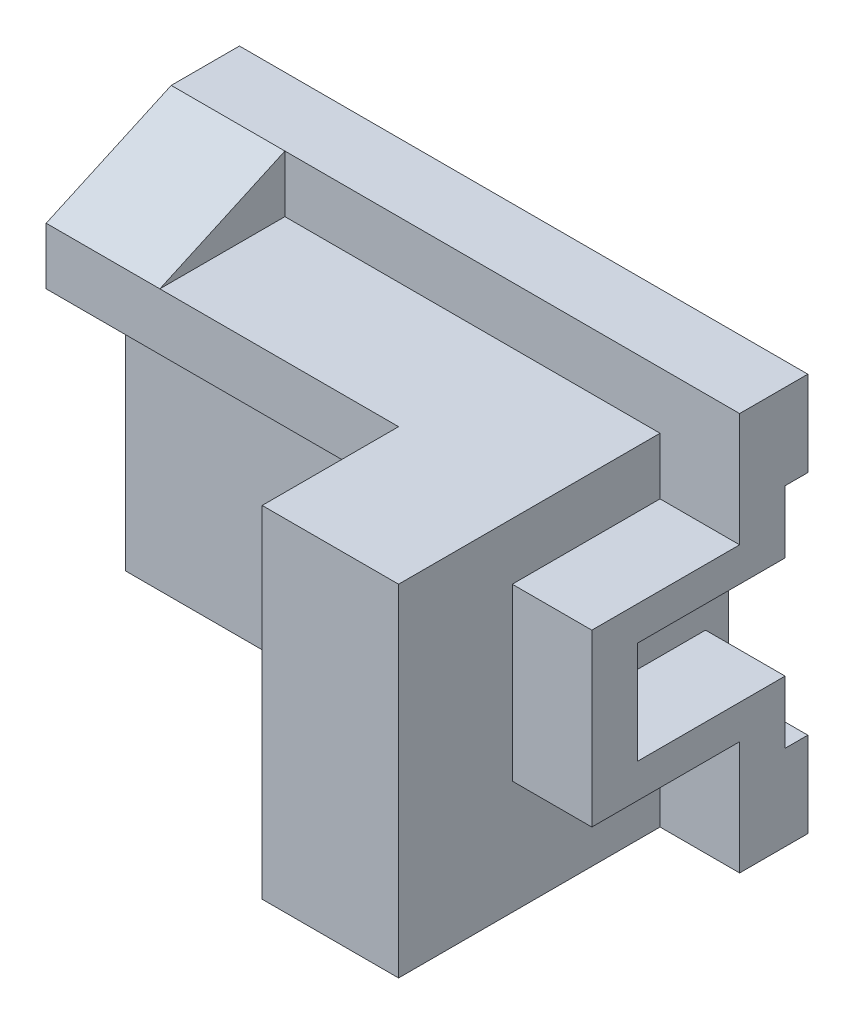
SolidWorks part; units mm, degrees
ref_plane "Спереди" through (0, 0, 0) normal (0, 0, 1) x (1, 0, 0)
ref_plane "Сверху" through (0, 0, 0) normal (0, 1, 0) x (1, 0, 0)
ref_plane "Справа" through (0, 0, 0) normal (1, 0, 0) x (0, 0, -1)
sketch "Эскиз1" plane through (0, 0, 0) normal (0, 0, 1) x (1, 0, 0)
  line L1 (-25, -17.5) -> (25, -17.5)
  line L2 (-25, -17.5) -> (-25, 17.5)
  line L3 (-25, 17.5) -> (25, 17.5)
  line L4 (25, -17.5) -> (25, 17.5)
  line L5 (-25, -17.5) -> (25, 17.5) construction
  line L6 (-25, 17.5) -> (25, -17.5) construction
  point P0 (0, 0)
  dimension "D1" = 35
  dimension "D2" = 50
extrude "Бобышка-Вытянуть1" add sketch "Эскиз1" along normal blind 6
sketch "Эскиз2" plane through (0, 0, 6) normal (0, 0, 1) x (1, 0, 0)
  line L0 (-25, -17.5) -> (25, -17.5) construction
  line L1 (18, -17.5) -> (6, -17.5)
  line L2 (18, -17.5) -> (18, 12.5)
  line L3 (18, 12.5) -> (6, 12.5)
  line L4 (6, -17.5) -> (6, 12.5)
  line L5 (25, -17.5) -> (25, 17.5) construction
  dimension "D1" = 7
  dimension "D2" = 12
  dimension "D3" = 30
extrude "Бобышка-Вытянуть2" add sketch "Эскиз2" along normal blind 23
sketch "Эскиз7" plane through (18, 0, 0) normal (1, 0, 0) x (0, 0, -1)
  line L0 (0, 0) -> (-29, 0) construction
  line L1 (-29, -17.5) -> (-29, 12.5) construction
  line L2 (-6, -17.5) -> (-6, 17.5) construction
  line L3 (-6, -7.5) -> (-19, -7.5)
  line L4 (-6, -7.5) -> (-6, 7.5)
  line L5 (-6, 7.5) -> (-19, 7.5)
  line L6 (-19, -7.5) -> (-19, 7.5)
  line L7 (-6, -7.5) -> (-19, 7.5) construction
  line L8 (-6, 7.5) -> (-19, -7.5) construction
  point P3 (-12.5, 0)
  dimension "D1" = 15
  dimension "D2" = 13
extrude "Бобышка-Вытянуть3" add sketch "Эскиз7" along normal up to surface (7 mm away) up to face at (25, 0, 3)
sketch "Эскиз8" plane through (25, 0, 0) normal (1, 0, 0) x (0, 0, -1)
  line L0 (0, 0) -> (-19, 0) construction
  line L1 (-19, 7.5) -> (-19, -7.5) construction
  line L2 (0, -17.5) -> (0, 17.5) construction
  line L3 (0, -4.5) -> (-15, -4.5)
  line L4 (0, -4.5) -> (0, 4.5)
  line L5 (0, 4.5) -> (-15, 4.5)
  line L6 (-15, -4.5) -> (-15, 4.5)
  line L7 (0, -4.5) -> (-15, 4.5) construction
  line L8 (0, 4.5) -> (-15, -4.5) construction
  line L9 (-6, 7.5) -> (-19, 7.5) construction
  line L11 (0, -10) -> (-2, -10)
  line L12 (0, -10) -> (0, 10)
  line L13 (0, 10) -> (-2, 10)
  line L14 (-2, -10) -> (-2, 10)
  line L15 (0, -10) -> (-2, 10) construction
  line L16 (0, 10) -> (-2, -10) construction
  point P5 (-7.5, 0)
  point P14 (-1, 0)
  line M1 (0, -17.5) -> (0, 17.5)
  dimension "D1" = 4
  dimension "D2" = 3
  dimension "D3" = 2
  dimension "D4" = 20
extrude "Вырез-Вытянуть4" cut sketch "Эскиз8" against normal up to surface (7 mm away) contours L3 L14 L5 L6 | L14 L11 L3 M1 | L14 L3 L5 M1 | L14 L5 L13 M1 up to face at (18, -2.1875, 16.4375)
sketch "Эскиз9" plane through (-25, 0, 0) normal (-1, 0, 0) x (0, 0, 1)
  line L0 (6, 17.5) -> (17, 12.5)
  line L1 (17, 12.5) -> (17, 7.5)
  line L2 (17, 7.5) -> (6, 7.5)
  line L3 (6, 12.5) -> (6, -17.5) construction
  line L4 (6, 7.5) -> (6, 17.5)
  dimension "D1" = 10
  dimension "D2" = 11
  dimension "D3" = 5
extrude "Бобышка-Вытянуть4" add sketch "Эскиз9" against normal up to surface (31 mm away) up to face at (6, 1.25, 20.375)
sketch "Эскиз11" plane through (6, 0, 0) normal (1, 0, 0) x (0, 0, -1)
  line L0 (-6, 7.5) -> (-6, 17.5) construction
  line L1 (-6, 12.5) -> (-17, 12.5)
  line L2 (-6, 12.5) -> (-6, 17.5)
  line L3 (-6, 17.5) -> (-17, 17.5)
  line L4 (-17, 12.5) -> (-17, 17.5)
  line L5 (-6, 17.5) -> (0, 17.5) construction
  line L6 (-17, -35.0001) -> (-17, 12.5) construction
extrude "Вырез-Вытянуть5" cut sketch "Эскиз11" against normal offset from surface (21 mm away) 10 up to face at (-25, 3.9286, 7.4286)
sketch "Эскиз12" plane through (0, 0, 6) normal (0, 0, 1) x (1, 0, 0)
  line L4 (6, -17.5) -> (6, 7.5)
  line L5 (6, -17.5) -> (6, 7.5)
  line L6 (6, 7.5) -> (-25, 7.5)
  line L7 (-25, -17.5) -> (6, -17.5)
  line L8 (6, 7.5) -> (-25, 7.5)
  line L9 (-25, 7.5) -> (-25, -17.5)
  line L10 (-25, 7.5) -> (-25, -17.5)
  line L11 (-25, -17.5) -> (6, -17.5)
  dimension "D1" = 0
extrude "Бобышка-Вытянуть5" add sketch "Эскиз12" along normal blind 4
